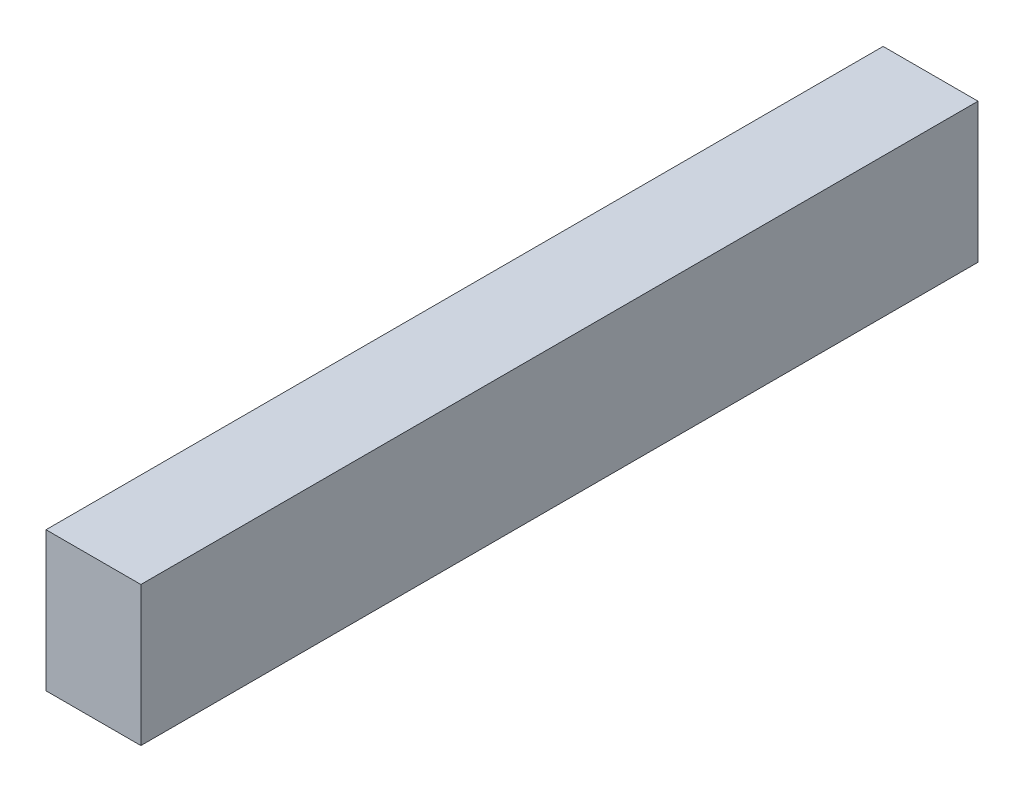
SolidWorks part; units mm, degrees
ref_plane "Front Plane" through (0, 0, 0) normal (0, 0, 1) x (1, 0, 0)
ref_plane "Top Plane" through (0, 0, 0) normal (0, 1, 0) x (1, 0, 0)
ref_plane "Right Plane" through (0, 0, 0) normal (1, 0, 0) x (0, 0, -1)
sketch "Sketch1" plane through (0, 0, 0) normal (0, 0, 1) x (1, 0, 0)
  line L1 (-17, 25) -> (17, 25)
  line L2 (-17, 25) -> (-17, -25)
  line L3 (-17, -25) -> (17, -25)
  line L4 (17, 25) -> (17, -25)
  line L5 (-17, 25) -> (17, -25) construction
  line L6 (-17, -25) -> (17, 25) construction
  point P0 (0, 0)
  dimension "D1" = 34
  dimension "D2" = 50
extrude "Boss-Extrude1" add sketch "Sketch1" along normal blind 300
sketch "Sketch3" plane through (-17, 0, 0) normal (-1, 0, 0) x (0, 0, 1)
  line L0 (300, 0) -> (290, 0) construction
  line L1 (300, 25) -> (300, -25) construction
  line L2 (290, 0) -> (220, 0)
  line L3 (220, 1.5) -> (220, -1.5)
  line L4 (290, 1.5) -> (290, -1.5)
  line L5 (220, 1.5) -> (290, 1.5)
  line L6 (220, -1.5) -> (290, -1.5)
  point P9 (220, 0)
  point P12 (290, 0)
  dimension "D1" = 10
  dimension "D2" = 3
  dimension "D3" = 70
extrude "Cut-Extrude1" cut sketch "Sketch3" against normal blind 25 contours L5 L3 L2 L4
sketch "Sketch4" plane through (-17, 0, 0) normal (-1, 0, 0) x (0, 0, 1)
  line L1 (150, 2.25) -> (220, 2.25)
  line L2 (150, 2.25) -> (150, -2.25)
  line L3 (150, -2.25) -> (220, -2.25)
  line L4 (220, 2.25) -> (220, -2.25)
  line L5 (220, 0) -> (217.4658, 0) construction
  line L6 (220, 1.5) -> (220, -1.5) construction
  point P5 (220, 0)
  dimension "D1" = 4.5
  dimension "D2" = 70
extrude "Cut-Extrude2" cut sketch "Sketch4" against normal blind 25
sketch "Sketch5" plane through (-17, 0, 0) normal (-1, 0, 0) x (0, 0, 1)
  line L0 (150, 0) -> (140.2666, 0) construction
  line L1 (80, 2.75) -> (150, 2.75)
  line L2 (80, 2.75) -> (80, -2.75)
  line L3 (80, -2.75) -> (150, -2.75)
  line L4 (150, 2.75) -> (150, -2.75)
  line L5 (150, 2.25) -> (150, -2.25) construction
  point P9 (150, 0)
  dimension "D1" = 5.5
  dimension "D2" = 70
extrude "Cut-Extrude3" cut sketch "Sketch5" against normal blind 25
sketch "Sketch6" plane through (-17, 0, 0) normal (-1, 0, 0) x (0, 0, 1)
  line L0 (60, 10) -> (60, -10)
  line L1 (60, -10) -> (80, -2.75)
  line L2 (60, 10) -> (80, 2.75)
  line L3 (80, 2.75) -> (80, -2.75) construction
  line L4 (60, 10) -> (0, 10)
  line L5 (0, 25) -> (0, -25) construction
  line L6 (0, 10) -> (0, -10)
  line L7 (0, -10) -> (60, -10)
  point P2 (80, 0)
  point P7 (60, 0)
  line M5 (0, 25) -> (0, -25)
  line M20 (80, -2.75) -> (80, 2.75)
  dimension "D1" = 20
  dimension "D2" = 20
extrude "Cut-Extrude4" cut sketch "Sketch6" against normal blind 25 contours L7 L0 L4 M5 | L2 L0 L1 M20
sketch "Sketch7" plane through (0, 2.75, 0) normal (0, -1, 0) x (-1, 0, 0)
  line L0 (-8, -80) -> (17, -150)
  line L1 (-8, -80) -> (17, -80) construction
  line L2 (-8, -60) -> (-8, -80) construction
  line L3 (17, -300) -> (17, 0) construction
  line L4 (17, -150) -> (-8, -150)
  line L5 (-8, -150) -> (-8, -80)
extrude "Boss-Extrude2" add sketch "Sketch7" along normal blind 1
sketch "Sketch9" plane through (0, 2.25, 0) normal (0, -1, 0) x (1, 0, 0)
  line L0 (-17, 220) -> (-17, 150) construction
  line L1 (-17, 220) -> (8, 220)
  line L4 (8, 220) -> (8, 150)
  line L5 (-17, 300) -> (-17, 0) construction
  line L6 (17, 300) -> (-17, 300) construction
  line L7 (-17, 220) -> (8, 150)
  dimension "D1" = 70
  dimension "D2" = 25
  dimension "D3" = 80
extrude "Boss-Extrude3" add sketch "Sketch9" along normal blind 1
sketch "Sketch10" plane through (0, 1.5, 0) normal (0, -1, 0) x (-1, 0, 0)
  line L0 (17, -290) -> (-8, -250)
  line L1 (17, -300) -> (17, 0) construction
  line L2 (17, -220) -> (17, -290) construction
  line L3 (-8, -250) -> (-8, -290)
  line L4 (-8, -290) -> (17, -290)
  line L5 (-17, -300) -> (17, -300) construction
  dimension "D1" = 10
  dimension "D2" = 40
  dimension "D3" = 25
extrude "Boss-Extrude4" add sketch "Sketch10" along normal blind 3
sketch "Sketch11" plane through (-17, 0, 0) normal (-1, 0, 0) x (0, 0, 1)
  line L0 (300, 0) -> (0, 0)
  line L1 (300, 25) -> (300, -25) construction
mirror "Mirror3" about plane through (0, 0, 0) normal (0, 1, 0) of "Boss-Extrude3", "Boss-Extrude2"
